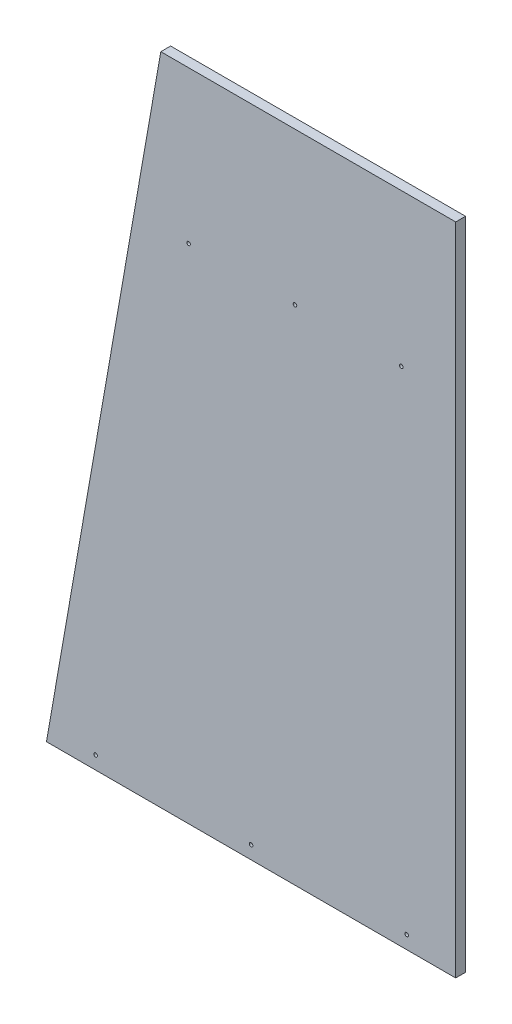
SolidWorks part; units mm, degrees
material "Дуб"
ref_plane "Front Plane" through (0, 0, 0) normal (0, 0, 1) x (1, 0, 0)
ref_plane "Top Plane" through (0, 0, 0) normal (0, 1, 0) x (1, 0, 0)
ref_plane "Right Plane" through (0, 0, 0) normal (1, 0, 0) x (0, 0, -1)
sketch "Эскиз1" plane through (0, 0, 0) normal (0, 0, 1) x (1, 0, 0)
  line L0 (0, 0) -> (69.8413, 400)
  line L1 (69.8413, 400) -> (250, 400)
  line L2 (250, 400) -> (250, 0)
  line L3 (250, 0) -> (0, 0)
  line L4 (55, 315) -> (250, 315) construction
  line L5 (53.6032, 307) -> (250, 307) construction
  circle A0 centre (86.8032, 307) radius 1.1
  circle A1 centre (151.8032, 307) radius 1.1
  circle A2 centre (30, 8) radius 1.1
  circle A3 centre (220, 8) radius 1.1
  circle A4 centre (125, 8) radius 1.1
  circle A5 centre (216.8032, 307) radius 1.1
  dimension "D6" = 2.2
  dimension "D7" = 33.2
  dimension "D9" = 93
  dimension "D10" = 65
  dimension "D11" = 8
  dimension "D12" = 30
  dimension "D13" = 30
  dimension "D15" = 65
  dimension "D1" = 85
  dimension "D2" = 195
  dimension "D3" = 250
  dimension "D4" = 400
  dimension "D5" = 90
  dimension "D8" = 163.1968
  dimension "D14" = 95
  dimension "D16" = 33.1968
extrude "Бобышка-Вытянуть1" add sketch "Эскиз1" along normal blind 6
